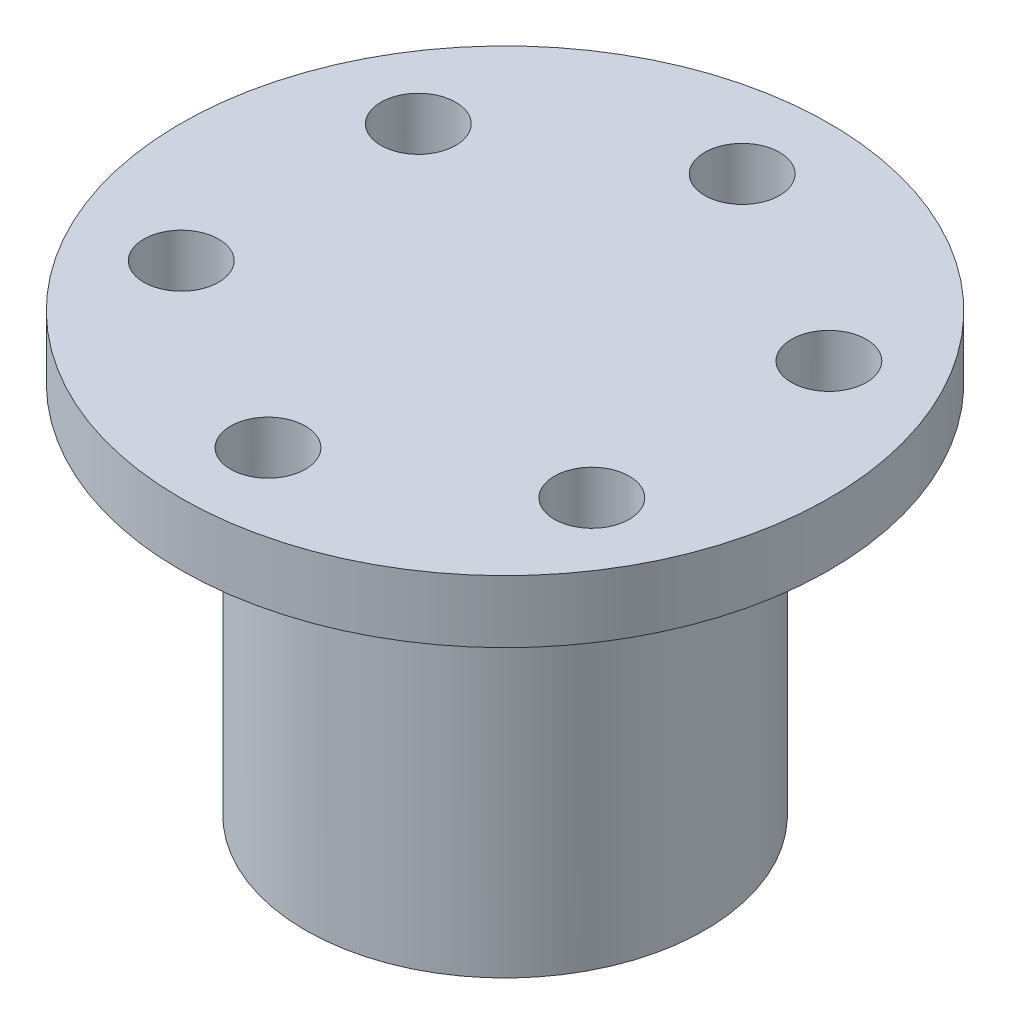
SolidWorks part; units mm, degrees
ref_plane "Front Plane" through (0, 0, 0) normal (0, 0, 1) x (1, 0, 0)
ref_plane "Top Plane" through (0, 0, 0) normal (0, 1, 0) x (1, 0, 0)
ref_plane "Right Plane" through (0, 0, 0) normal (1, 0, 0) x (0, 0, -1)
sketch "Sketch1" plane through (0, 0, 0) normal (0, 1, 0) x (1, 0, 0)
  circle A0 centre (0, 0) radius 26
  point P18 (0, 0)
  dimension "D1" = 52
extrude "Boss-Extrude1" add sketch "Sketch1" along normal blind 5 contours A0
sketch "Sketch2" plane through (0, 5, 0) normal (0, 1, 0) x (1, 0, 0)
  line L0 (0, 0) -> (0, 19) construction
  circle A0 centre (0, 0) radius 11.25
  circle A1 centre (0, 19) radius 3
  circle A2 centre (16.4545, 9.5) radius 3
  circle A3 centre (16.4545, -9.5) radius 3
  circle A4 centre (0, -19) radius 3
  circle A5 centre (-16.4545, -9.5) radius 3
  circle A6 centre (-16.4545, 9.5) radius 3
  dimension "D1" = 22.5
  dimension "D2" = 6
  dimension "D5" = 19
  dimension "D4" = 6
sketch "Sketch11" plane through (0, 5, 0) normal (0, 1, 0) x (1, 0, 0)
  circle A0 centre (-16.4545, -9.5) radius 3
  circle A1 centre (-16.4545, 9.5) radius 3
  circle A2 centre (0, 19) radius 3
  circle A3 centre (16.4545, 9.5) radius 3
  circle A4 centre (16.4545, -9.5) radius 3
  circle A5 centre (0, -19) radius 3
  point P15 (0, 0)
extrude "Cut-Extrude7" cut sketch "Sketch11" against normal through all
sketch "Sketch4" plane through (0, 5, 0) normal (0, 1, 0) x (1, 0, 0)
  circle A0 centre (0, 0) radius 16
  dimension "D1" = 32
extrude "Boss-Extrude4" add sketch "Sketch4" against normal blind 30 from surface at -5 contours A0 starting at face at (0, 0, 22)
sketch "Sketch10" plane through (0, -30, 0) normal (0, -1, 0) x (1, 0, 0)
  line L1 (-9, -9) -> (9, -9)
  line L2 (-9, -9) -> (-9, 9)
  line L3 (-9, 9) -> (9, 9)
  line L4 (9, -9) -> (9, 9)
  line L5 (-9, -9) -> (9, 9) construction
  line L6 (-9, 9) -> (9, -9) construction
  point P0 (0, 0)
  point P3 (0, 12.5)
  point P25 (0, 0)
  dimension "D1" = 18
  dimension "D2" = 18
extrude "Cut-Extrude8" cut sketch "Sketch10" against normal blind 24.25
